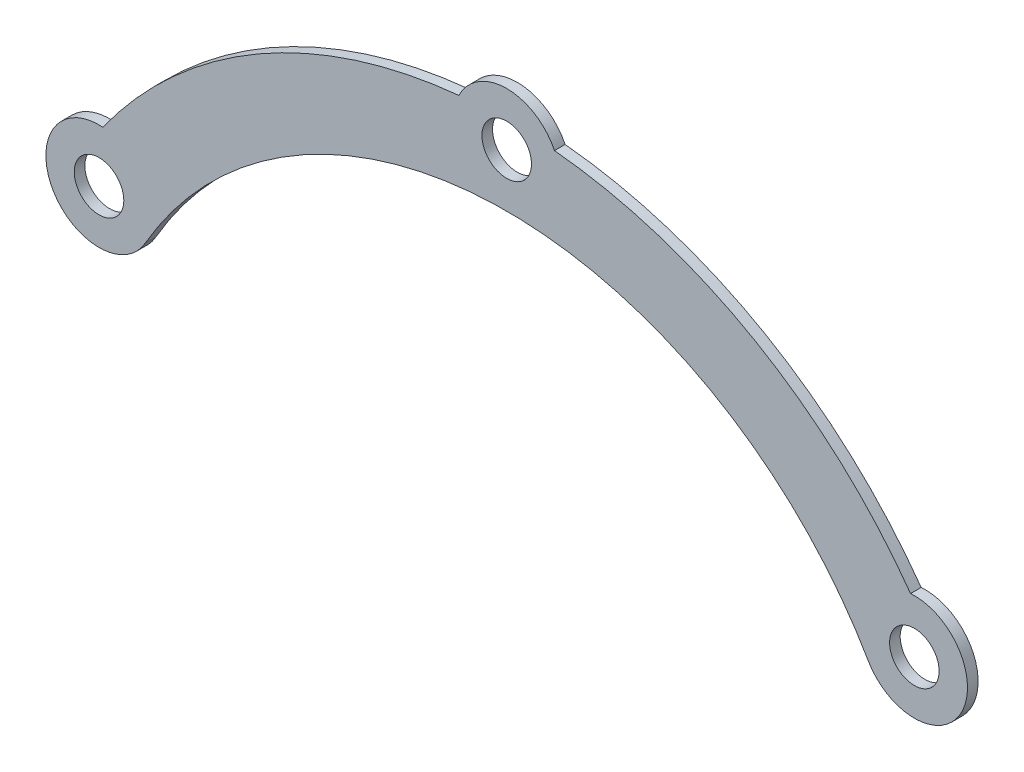
SolidWorks part; units mm, degrees
ref_plane "Alzado" through (0, 0, 0) normal (0, 0, 1) x (1, 0, 0)
ref_plane "Planta" through (0, 0, 0) normal (0, 1, 0) x (1, 0, 0)
ref_plane "Vista lateral" through (0, 0, 0) normal (1, 0, 0) x (0, 0, -1)
sketch "Croquis1" plane through (0, 0, 0) normal (0, 0, 1) x (1, 0, 0)
  line L0 (0, 0) -> (0, 199.486) construction
  line L1 (0, 0) -> (-73.1402, 42.2275) construction
  line L2 (0, 0) -> (73.1402, 42.2275) construction
  circle A0 centre (0, 0) radius 84.455 construction
  arc A1 (-72.4571, 51.733) -> (-64.887, 37.4625) centre (-73.1402, 42.2275) ccw
  circle A2 centre (-73.1402, 42.2275) radius 4.445
  arc A3 (64.887, 37.4625) -> (-64.887, 37.4625) centre (0, 0) ccw
  circle A4 centre (73.1402, 42.2275) radius 4.445
  arc A5 (64.887, 37.4625) -> (72.4571, 51.733) centre (73.1402, 42.2275) ccw
  circle A6 centre (0, 84.455) radius 4.445
  arc A7 (8.5735, 88.6162) -> (-8.5735, 88.6162) centre (0, 84.455) ccw
  arc A8 (-8.5735, 88.6162) -> (-72.4571, 51.733) centre (0, 0) ccw
  arc A9 (72.4571, 51.733) -> (8.5735, 88.6162) centre (0, 0) ccw
  dimension "D1" = 168.91
  dimension "D2" = 8.89
  dimension "D3" = 19.06
  dimension "D6" = 89.03
  dimension "D7" = 42.2275
  dimension "D4" = 60
  dimension "D5" = 60
extrude "Saliente-Extruir1" add sketch "Croquis1" along normal blind 1.905
